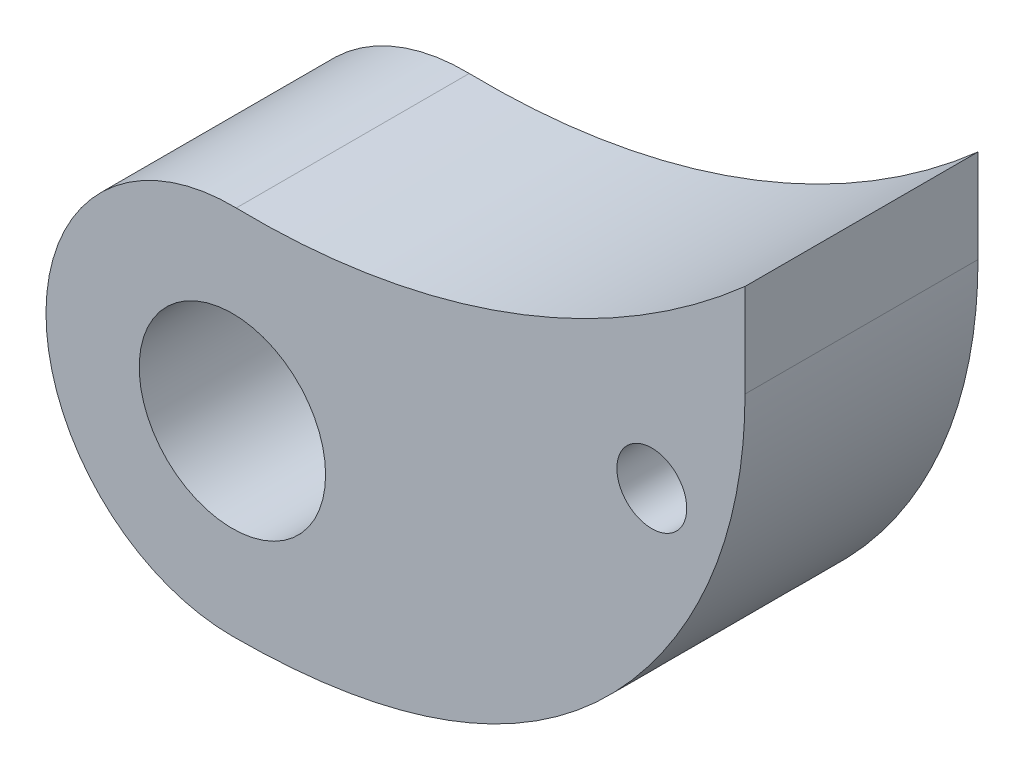
SolidWorks part; units mm, degrees
ref_plane "Front Plane" through (0, 0, 0) normal (0, 0, 1) x (1, 0, 0)
ref_plane "Top Plane" through (0, 0, 0) normal (0, 1, 0) x (1, 0, 0)
ref_plane "Right Plane" through (0, 0, 0) normal (1, 0, 0) x (0, 0, -1)
sketch "Sketch1" plane through (0, 0, 0) normal (0, 0, 1) x (1, 0, 0)
  line L0 (0, 0) -> (9, 0) construction
  line L1 (-4, 0) -> (11, 0) construction
  line L2 (11, 8) -> (11, 6)
  line L3 (3.3616, -4) -> (-3.3616, -4) construction
  line L4 (11, 7.8758) -> (11, 4.1135) construction
  line L5 (9, 0) -> (9, 6.4958) construction
  circle A0 centre (0, 0) radius 2
  arc A1 (0.0824, 3.9992) -> (0, -4) centre (0, 0) ccw
  arc A2 (0.0824, 3.9992) -> (11, 8) centre (0.4122, 19.9958) ccw
  circle A3 centre (9, 3.2479) radius 0.75
  spline S0 degree 3 poles (0, -4) (4.202, -4) (8.9833, -1.5566) (11, 3.6486) (11, 6) knots 0 0 0 0 0.608954 1 1 1 1
  point P7 (11, 8)
  dimension "D1" = 4
  dimension "D2" = 8
  dimension "D6" = 16
  dimension "D8" = 1.5
  dimension "D3" = 9
  dimension "D4" = 15
  dimension "D5" = 8
  dimension "D7" = 2
extrude "Boss-Extrude1" add sketch "Sketch1" along normal blind 5
